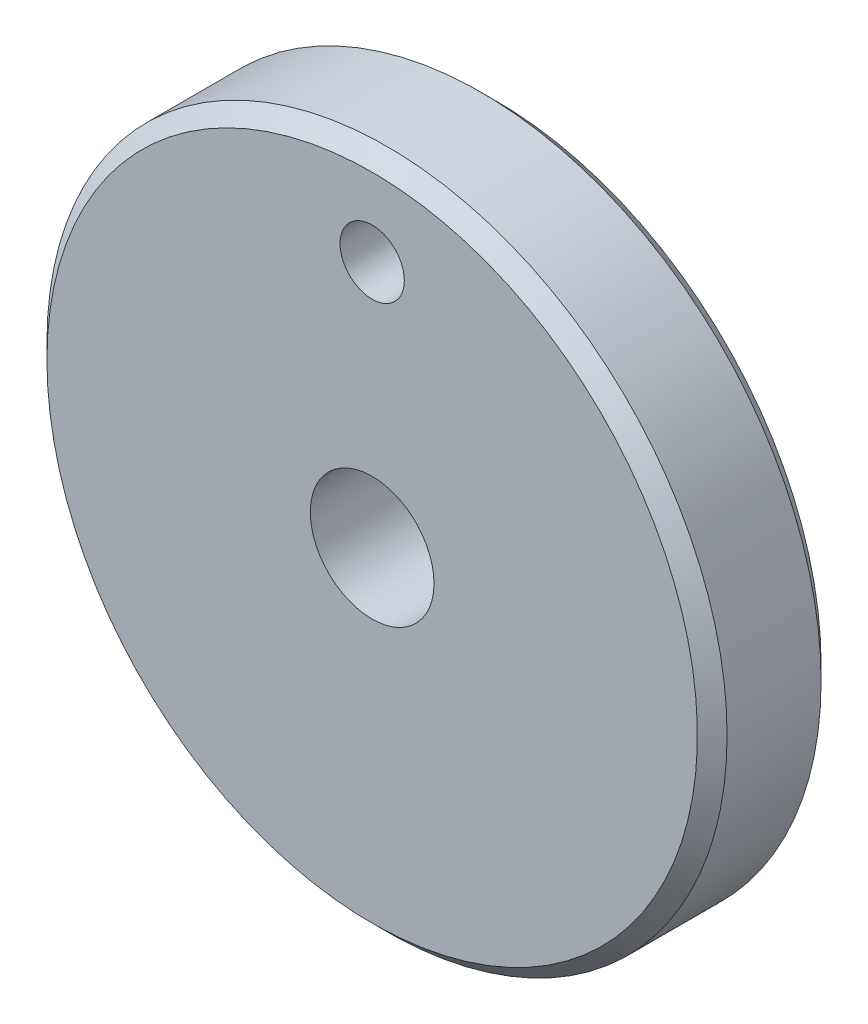
SolidWorks part; units mm, degrees
ref_plane "Front Plane" through (0, 0, 0) normal (0, 0, 1) x (1, 0, 0)
ref_plane "Top Plane" through (0, 0, 0) normal (0, 1, 0) x (1, 0, 0)
ref_plane "Right Plane" through (0, 0, 0) normal (1, 0, 0) x (0, 0, -1)
sketch "Sketch1" plane through (0, 0, 0) normal (0, 0, 1) x (1, 0, 0)
  circle A0 centre (0, 0) radius 17.4625
  circle A1 centre (0, 0) radius 3.175
  dimension "D1" = 34.925
  dimension "D2" = 6.35
extrude "Boss-Extrude1" add sketch "Sketch1" along normal blind 6.35
sketch "Sketch3" plane through (0, 0, 6.35) normal (0, 0, 1) x (1, 0, 0)
  circle A0 centre (0, 12.7) radius 1.651
  circle A1 centre (0, 0) radius 3.175 construction
  dimension "D1" = 3.302
  dimension "D2" = 12.7
extrude "Cut-Extrude3" cut sketch "Sketch3" against normal blind 16.51
chamfer "Chamfer1" distance 0.762 angle 45 1 edges at (17.4625, 0, 6.35)
chamfer "Chamfer2" distance 0.762 angle 45 1 edges at (17.4625, 0, 0)
